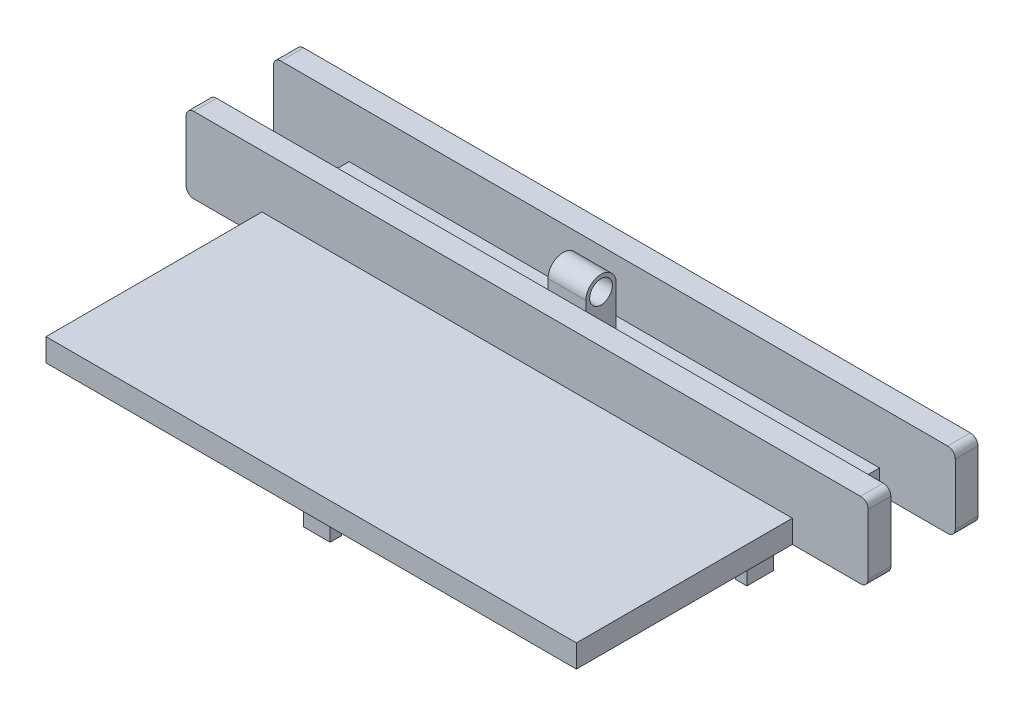
SolidWorks part; units mm, degrees
ref_plane "Front Plane" through (0, 0, 0) normal (0, 0, 1) x (1, 0, 0)
ref_plane "Top Plane" through (0, 0, 0) normal (0, 1, 0) x (1, 0, 0)
ref_plane "Right Plane" through (0, 0, 0) normal (1, 0, 0) x (0, 0, -1)
sketch "Sketch1" plane through (0, 0, 0) normal (0, 1, 0) x (1, 0, 0)
  line L1 (-35, 25) -> (35, 25)
  line L2 (-35, 25) -> (-35, -25)
  line L3 (-35, -25) -> (35, -25)
  line L4 (35, 25) -> (35, -25)
  line L5 (-35, 25) -> (35, -25) construction
  line L6 (-35, -25) -> (35, 25) construction
  point P0 (0, 0)
  dimension "D1" = 50
  dimension "D2" = 70
extrude "Boss-Extrude1" add sketch "Sketch1" along normal blind 3
sketch "Sketch2" plane through (0, 0, 0) normal (0, -1, 0) x (1, 0, 0)
  line L4 (0, -23.5) -> (0, 23.5) construction
  line L5 (-1.75, 24.25) -> (1.75, 24.25)
  line L6 (-1.75, 24.25) -> (-1.75, 22.75)
  line L7 (-1.75, 22.75) -> (1.75, 22.75)
  line L8 (33.5, -23.5) -> (33.5, 23.5)
  line L9 (33.5, 23.5) -> (-33.5, 23.5)
  line L10 (-33.5, 23.5) -> (-33.5, -23.5)
  line L11 (-33.5, -23.5) -> (33.5, -23.5)
  line L12 (33.5, -23.5) -> (33.5, 23.5) construction
  line L13 (33.5, 23.5) -> (-33.5, 23.5) construction
  line L14 (-33.5, 23.5) -> (-33.5, -23.5) construction
  line L15 (-33.5, -23.5) -> (33.5, -23.5) construction
  line L16 (1.75, 24.25) -> (1.75, 22.75)
  line L17 (-1.75, 24.25) -> (1.75, 22.75) construction
  line L18 (-1.75, 22.75) -> (1.75, 24.25) construction
  line L19 (34.25, -1.75) -> (32.75, -1.75)
  line L20 (-34.25, 1.75) -> (-32.75, 1.75)
  line L21 (-34.25, 1.75) -> (-34.25, -1.75)
  line L22 (-34.25, -1.75) -> (-32.75, -1.75)
  line L23 (-32.75, 1.75) -> (-32.75, -1.75)
  line L24 (-34.25, 1.75) -> (-32.75, -1.75) construction
  line L25 (-34.25, -1.75) -> (-32.75, 1.75) construction
  line L26 (32.75, 1.75) -> (32.75, -1.75)
  line L27 (34.25, 1.75) -> (32.75, 1.75)
  line L28 (34.25, 1.75) -> (34.25, -1.75)
  point P0 (0, 23.5)
  point P9 (-33.5, 0)
  dimension "D2" = 1.5
  dimension "D3" = 3.5
  dimension "D4" = 23.5
  dimension "D1" = 1.5
extrude "Boss-Extrude2" add sketch "Sketch2" along normal blind 2.5
ref_plane "Plane1" through (0, 0, -15) normal (0, 0, 1) x (1, 0, 0)
sketch "Sketch5" plane through (0, 0, -15) normal (0, 0, 1) x (1, 0, 0)
  line L0 (35, 3) -> (35, 0) construction
  line L1 (-35, 3) -> (-35, 0) construction
  line L2 (-35, 3) -> (35, 3) construction
  line L3 (35, 3) -> (35, 0)
  line L4 (-35, 3) -> (-35, 0)
  line L5 (-35, 3) -> (35, 3)
  line L6 (-35, 0) -> (-45, 0)
  line L7 (-45, 0) -> (-45, 10)
  line L8 (-45, 10) -> (45, 10)
  line L9 (45, 10) -> (45, 0)
  line L10 (45, 0) -> (35, 0)
  dimension "D1" = 10
  dimension "D2" = 10
extrude "Boss-Extrude3" add sketch "Sketch5" against normal blind 3
fillet "Fillet1" radius 1 4 edges at (45, 0, -16.5) (45, 10, -16.5) (-45, 0, -16.5) (-45, 10, -16.5)
pattern_linear "LPattern1" count 2 spacing 11.5 along (0, 0, 1) of "Boss-Extrude3", "Fillet1"
ref_plane "Plane3" through (0, 0, 0) normal (-1, 0, 0) x (0, 0, 1)
sketch "Sketch6" plane through (0, 0, 0) normal (-1, 0, 0) x (0, 0, 1)
  line L0 (-10.75, 0) -> (-10.75, 9) construction
  line L1 (-15, 0) -> (-6.5, 0) construction
  line L2 (-12.75, 9) -> (-12.75, 0)
  line L3 (-8.75, 9) -> (-8.75, 0)
  line L4 (-8.75, 0) -> (-12.75, 0)
  circle A0 centre (-10.75, 9) radius 2
  circle A1 centre (-10.75, 9) radius 1.5
  point P5 (-9.6137, 0)
  point P6 (-9.75, 9)
  point P7 (-11.75, 0)
  point P8 (-11.75, 9)
  dimension "D2" = 4
  dimension "D1" = 9
  dimension "D5" = 0.5
extrude "Boss-Extrude4" add sketch "Sketch6" along normal mid plane 5 contours L4 L0 A0 L2 | L0 L4 L3 A0 | A1
